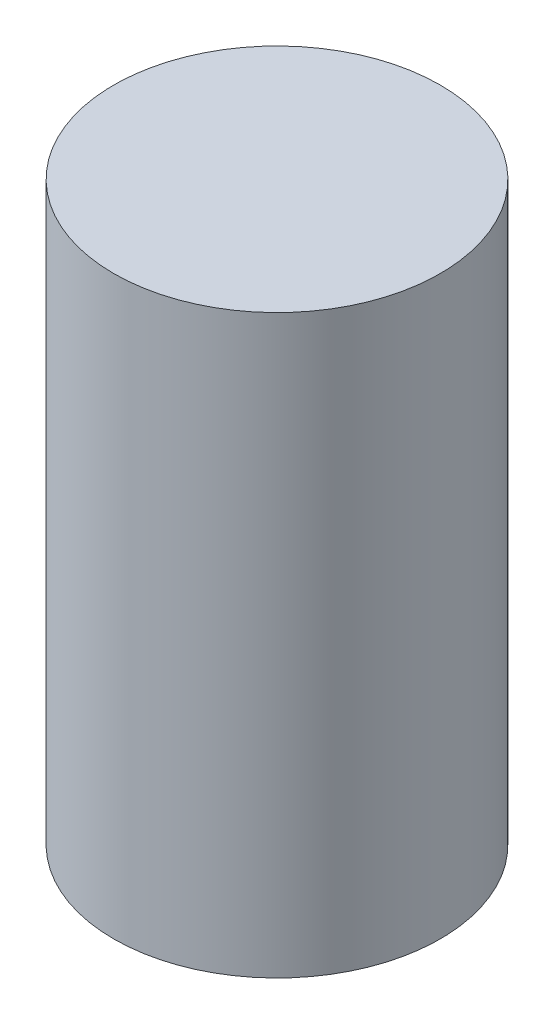
SolidWorks part; units mm, degrees
ref_plane "Front" through (0, 0, 0) normal (0, 0, 1) x (1, 0, 0)
ref_plane "Top" through (0, 0, 0) normal (0, 1, 0) x (1, 0, 0)
ref_plane "Right" through (0, 0, 0) normal (1, 0, 0) x (0, 0, -1)
sketch "Sketch1" plane through (0, 0, 0) normal (0, 1, 0) x (1, 0, 0)
  circle A0 centre (0, 0) radius 25.5
  circle A1 centre (0, 0) radius 24
  circle A2 centre (0, 0) radius 23
extrude "Boss-Extrude1" add sketch "Sketch1" along normal blind 90 contours A0
